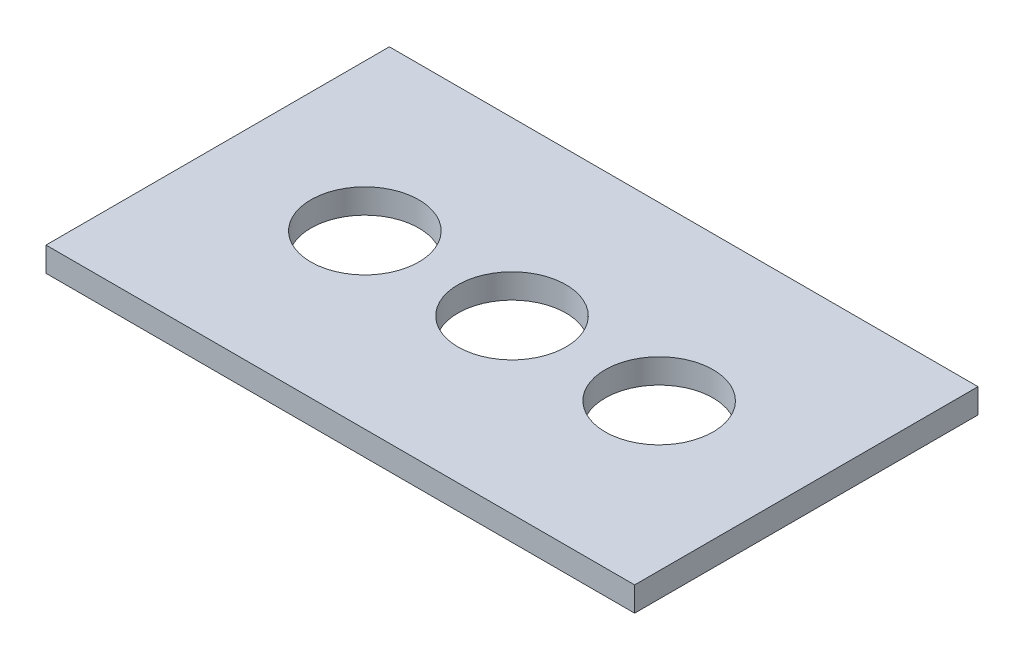
SolidWorks part; units mm, degrees
ref_plane "Front Plane" through (0, 0, 0) normal (0, 0, 1) x (1, 0, 0)
ref_plane "Top Plane" through (0, 0, 0) normal (0, 1, 0) x (1, 0, 0)
ref_plane "Right Plane" through (0, 0, 0) normal (1, 0, 0) x (0, 0, -1)
sketch "Sketch1" plane through (0, 0, 0) normal (0, 1, 0) x (1, 0, 0)
  line L1 (0, 0) -> (120, 0)
  line L2 (0, 0) -> (0, -70)
  line L3 (0, -70) -> (120, -70)
  line L4 (120, 0) -> (120, -70)
  dimension "D1" = 120
  dimension "D2" = 70
extrude "Boss-Extrude1" add sketch "Sketch1" along normal blind 5
sketch "Sketch2" plane through (0, 5, 0) normal (0, 1, 0) x (1, 0, 0)
  line L1 (0, -35) -> (120, -35) construction
  line L3 (0, 0) -> (0, -70) construction
  line L4 (120, -70) -> (120, 0) construction
  circle A3 centre (30, -35) radius 11
  circle A4 centre (60, -35) radius 11
  circle A5 centre (90, -35) radius 11
  dimension "D1" = 22
  dimension "D2" = 30
  dimension "D3" = 30
  dimension "D4" = 30
extrude "Cut-Extrude1" cut sketch "Sketch2" against normal through all
